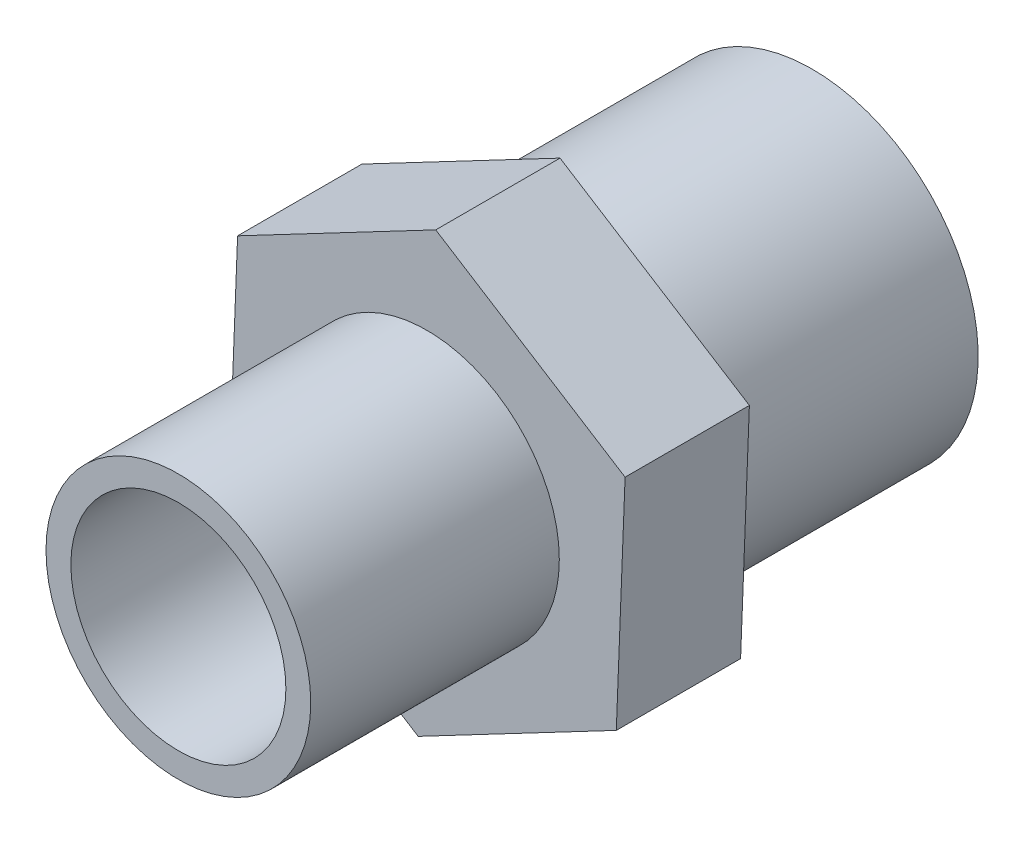
SolidWorks part; units mm, degrees
ref_plane "Front Plane" through (0, 0, 0) normal (0, 0, 1) x (1, 0, 0)
ref_plane "Top Plane" through (0, 0, 0) normal (0, 1, 0) x (1, 0, 0)
ref_plane "Right Plane" through (0, 0, 0) normal (1, 0, 0) x (0, 0, -1)
sketch "Sketch1" plane through (0, 0, 0) normal (0, 0, 1) x (1, 0, 0)
  circle A0 centre (0, 0) radius 13.35
  dimension "D1" = 26.7
extrude "Extrude-Thin1" add sketch "Sketch1" along normal mid plane 26 thin thin type one direction reverse wall 2
sketch "Sketch2" plane through (0, 0, 13) normal (0, 0, 1) x (1, 0, 0)
  line L1 (15.9422, 8.3873) -> (0.7074, 18)
  line L2 (0.7074, 18) -> (-15.2347, 9.6127)
  line L3 (-15.2347, 9.6127) -> (-15.9422, -8.3873)
  line L4 (-15.9422, -8.3873) -> (-0.7074, -18)
  line L5 (-0.7074, -18) -> (15.2347, -9.6127)
  line L6 (15.2347, -9.6127) -> (15.9422, 8.3873)
  circle A0 centre (0, 0) radius 15.6005 construction
  dimension "D1" = 18
extrude "Boss-Extrude1" add sketch "Sketch2" along normal mid plane 10
sketch "Sketch3" plane through (0, 0, 18) normal (0, 0, 1) x (1, 0, 0)
  circle A0 centre (0, 0) radius 10.65
  dimension "D1" = 21.3
extrude "Extrude-Thin2" add sketch "Sketch3" along normal blind 20 thin thin type one direction reverse wall 2
